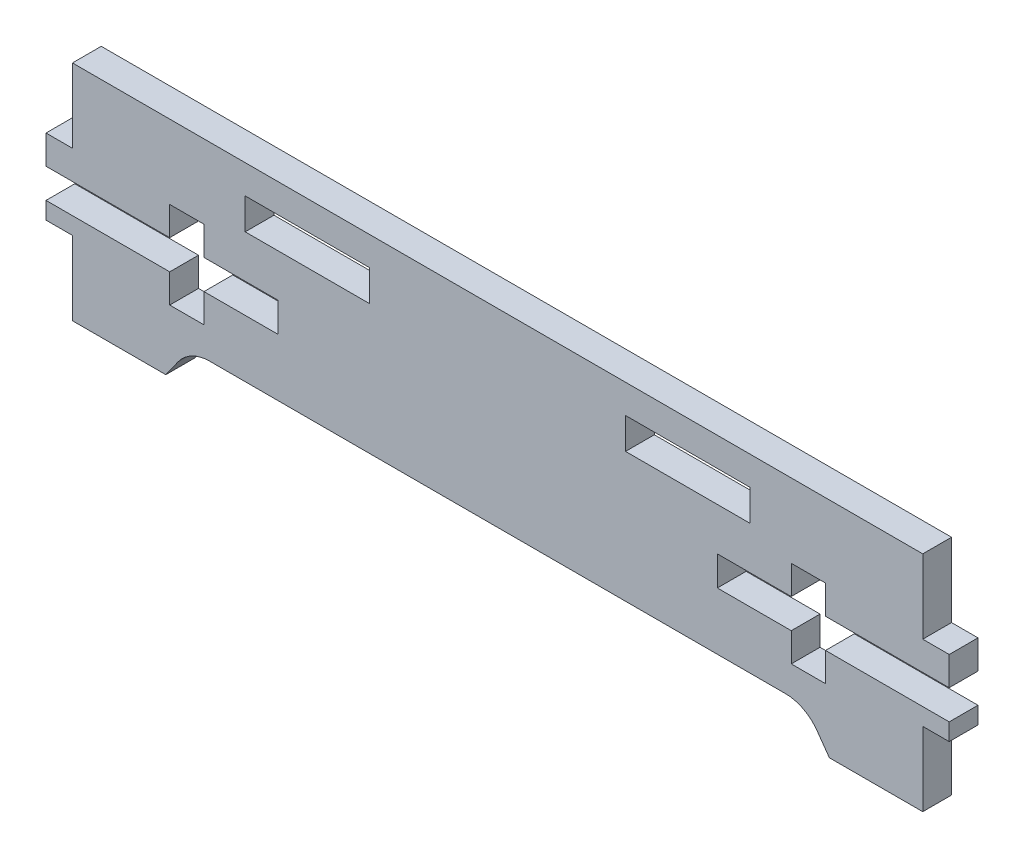
SolidWorks part; units mm, degrees
ref_plane "Front Plane" through (0, 0, 0) normal (0, 0, 1) x (1, 0, 0)
ref_plane "Top Plane" through (0, 0, 0) normal (0, 1, 0) x (1, 0, 0)
ref_plane "Right Plane" through (0, 0, 0) normal (1, 0, 0) x (0, 0, -1)
sketch "Sketch2" plane through (0, 0, 0) normal (0, 0, 1) x (1, 0, 0)
  line L0 (0, 38.7195) -> (0, -42.6567) construction
  line L1 (-54.64, 19.61) -> (54.64, 19.61)
  line L2 (54.64, 19.61) -> (54.64, 10.11)
  line L3 (54.64, 10.11) -> (58.04, 10.11)
  line L4 (58.04, 2.61) -> (58.04, 0.41)
  line L5 (58.04, 2.61) -> (42.14, 2.61)
  line L6 (58.04, 10.11) -> (58.04, 6.41)
  line L7 (42.14, 10.11) -> (37.74, 10.11)
  line L8 (42.14, 10.11) -> (42.14, 6.41)
  line L9 (37.74, 6.41) -> (28.24, 6.41)
  line L10 (0, 4.51) -> (75.8333, 4.51) construction
  line L11 (37.74, 2.61) -> (28.24, 2.61)
  line L12 (37.74, 2.61) -> (37.74, -1.09)
  line L13 (42.14, -1.09) -> (37.74, -1.09)
  line L14 (37.74, 6.41) -> (37.74, 10.11)
  line L15 (58.04, 6.41) -> (42.14, 6.41)
  line L16 (42.14, 2.61) -> (42.14, -1.09)
  line L17 (58.04, 0.41) -> (54.64, 0.41)
  line L18 (54.64, 0.41) -> (54.64, -9.09)
  line L19 (54.64, -9.09) -> (42.64, -9.09)
  line L20 (42.64, -9.09) -> (39.5723, -4.7693)
  line L21 (39.5723, -4.7693) -> (-39.5723, -4.7693)
  line L22 (28.24, 6.41) -> (28.24, 2.61)
  line L23 (-42.64, -9.09) -> (-39.5723, -4.7693)
  line L24 (-54.64, -9.09) -> (-42.64, -9.09)
  line L25 (-54.64, 0.41) -> (-54.64, -9.09)
  line L26 (-58.04, 0.41) -> (-54.64, 0.41)
  line L27 (-58.04, 2.61) -> (-58.04, 0.41)
  line L28 (-58.04, 2.61) -> (-42.14, 2.61)
  line L29 (-42.14, 2.61) -> (-42.14, -1.09)
  line L30 (-42.14, -1.09) -> (-37.74, -1.09)
  line L31 (-37.74, 2.61) -> (-37.74, -1.09)
  line L32 (-37.74, 2.61) -> (-28.24, 2.61)
  line L33 (-28.24, 6.41) -> (-28.24, 2.61)
  line L34 (-37.74, 6.41) -> (-28.24, 6.41)
  line L35 (-37.74, 6.41) -> (-37.74, 10.11)
  line L36 (-42.14, 10.11) -> (-37.74, 10.11)
  line L37 (-42.14, 10.11) -> (-42.14, 6.41)
  line L38 (-58.04, 6.41) -> (-42.14, 6.41)
  line L39 (-58.04, 10.11) -> (-58.04, 6.41)
  line L40 (-54.64, 10.11) -> (-58.04, 10.11)
  line L41 (-54.64, 19.61) -> (-54.64, 10.11)
  point P29 (0, -4.7693)
  point P47 (0, 19.61)
  dimension "D1" = 54.64
  dimension "D2" = 9.5
  dimension "D3" = 3.7
  dimension "D4" = 15.9
  dimension "D5" = 3.7
  dimension "D6" = 9.5
  dimension "D7" = 4.4
  dimension "D8" = 6
  dimension "D9" = 3.4
  dimension "D10" = 9.5
  dimension "D11" = 3.8
  dimension "D12" = 12
  dimension "D13" = 3.4
extrude "Boss-Extrude1" add sketch "Sketch2" along normal blind 3.7
fillet "Fillet1" radius 5 2 edges at (39.5723, -4.7693, 1.85) (-39.5723, -4.7693, 1.85)
sketch "Sketch3" plane through (0, 0, 3.7) normal (0, 0, 1) x (1, 0, 0)
  line L0 (0, 19.61) -> (0, -9.4252) construction
  line L1 (54.64, 19.61) -> (-54.64, 19.61) construction
  line L2 (54.64, 10.11) -> (54.64, 19.61) construction
  line L3 (32.44, 11.91) -> (16.44, 11.91)
  line L4 (32.44, 11.91) -> (32.44, 15.91)
  line L5 (32.44, 15.91) -> (16.44, 15.91)
  line L6 (16.44, 11.91) -> (16.44, 15.91)
  line L7 (32.44, 11.91) -> (16.44, 15.91) construction
  line L8 (32.44, 15.91) -> (16.44, 11.91) construction
  line L9 (-32.44, 15.91) -> (-16.44, 15.91)
  line L10 (-16.44, 11.91) -> (-16.44, 15.91)
  line L11 (-32.44, 11.91) -> (-16.44, 11.91)
  line L12 (-32.44, 11.91) -> (-32.44, 15.91)
  point P5 (24.44, 13.91)
  dimension "D1" = 22.2
  dimension "D2" = 3.7
  dimension "D3" = 4
  dimension "D4" = 16
extrude "Cut-Extrude1" cut sketch "Sketch3" against normal through all
